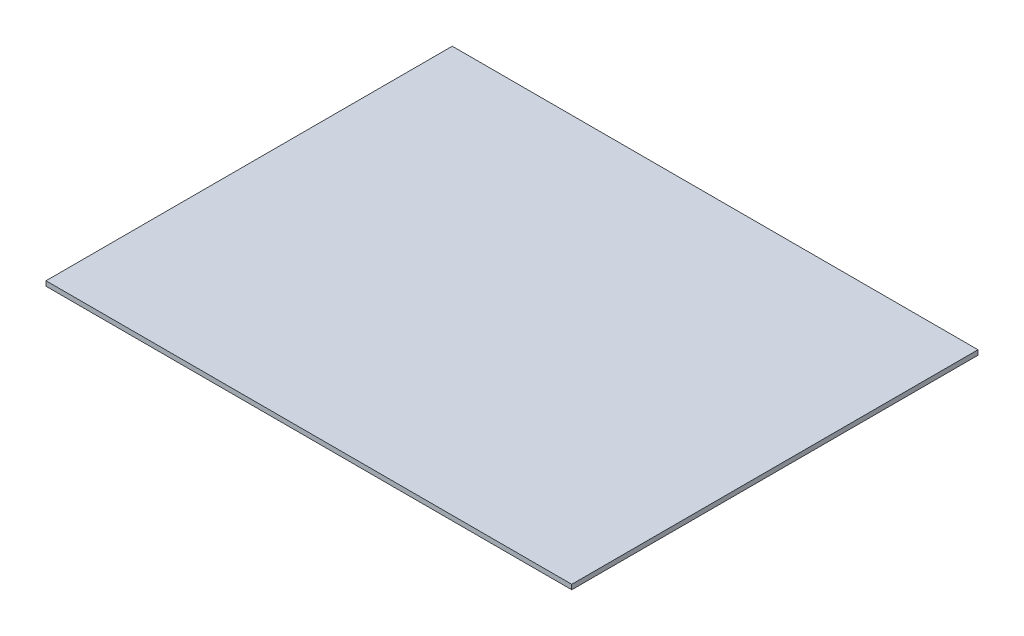
SolidWorks part; units mm, degrees
ref_plane "Front Plane" through (0, 0, 0) normal (0, 0, 1) x (1, 0, 0)
ref_plane "Top Plane" through (0, 0, 0) normal (0, 1, 0) x (1, 0, 0)
ref_plane "Right Plane" through (0, 0, 0) normal (1, 0, 0) x (0, 0, -1)
sketch "Sketch1" plane through (0, 0, 0) normal (0, 1, 0) x (1, 0, 0)
  line L1 (-185.2576, 44.8746) -> (94.1424, 44.8746)
  line L2 (-185.2576, 44.8746) -> (-185.2576, -171.0254)
  line L3 (-185.2576, -171.0254) -> (94.1424, -171.0254)
  line L4 (94.1424, 44.8746) -> (94.1424, -171.0254)
  dimension "D1" = 279.4
  dimension "D2" = 215.9
extrude "Boss-Extrude1" add sketch "Sketch1" along normal blind 2.54 contours L3 L4 L1 L2
